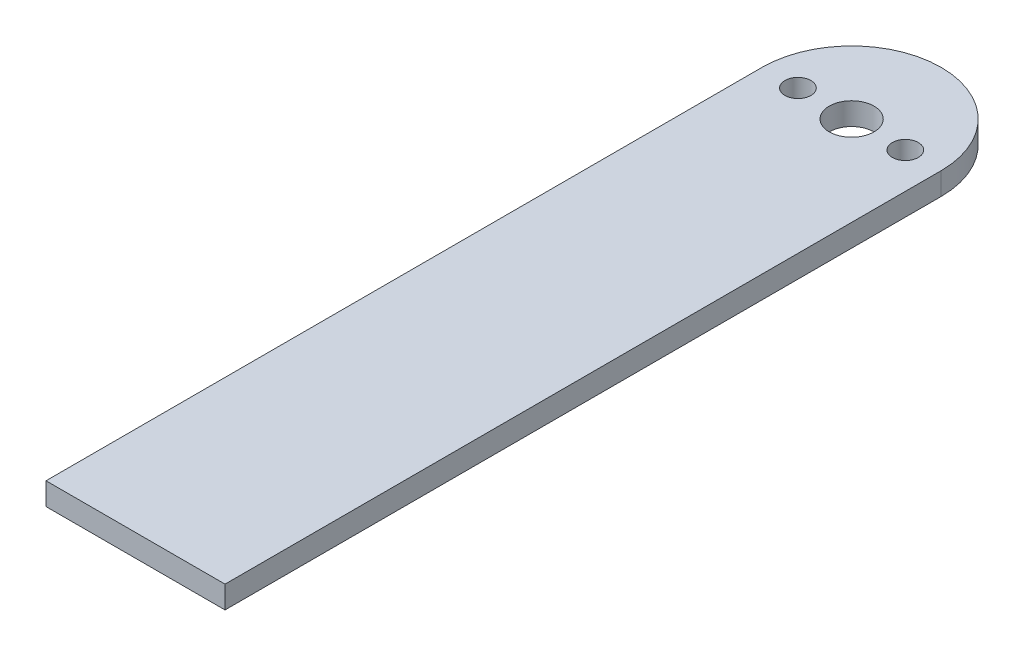
SolidWorks part; units mm, degrees
ref_plane "Front Plane" through (0, 0, 0) normal (0, 0, 1) x (1, 0, 0)
ref_plane "Top Plane" through (0, 0, 0) normal (0, 1, 0) x (1, 0, 0)
ref_plane "Right Plane" through (0, 0, 0) normal (1, 0, 0) x (0, 0, -1)
sketch "Sketch1" plane through (0, 0, 0) normal (0, 1, 0) x (1, 0, 0)
  line L0 (-12.7, 0) -> (-12.7, -101.6)
  line L1 (12.7, 0) -> (12.7, -101.6)
  line L2 (-12.7, -101.6) -> (12.7, -101.6)
  line L3 (-12.7, 0) -> (12.7, 0) construction
  arc A0 (12.7, 0) -> (-12.7, 0) centre (0, 0) ccw
  arc A1 (-12.7, 0) -> (12.7, 0) centre (0, 0) ccw construction
  circle A2 centre (0, 0) radius 3.175
  circle A3 centre (-7.62, 0) radius 1.8415
  circle A4 centre (7.62, 0) radius 1.8415
  dimension "D1" = 25.4
  dimension "D3" = 6.35
  dimension "D4" = 3.683
  dimension "D2" = 101.6
  dimension "D5" = 7.62
  dimension "D6" = 7.62
extrude "Boss-Extrude1" add sketch "Sketch1" along normal blind 3.175
